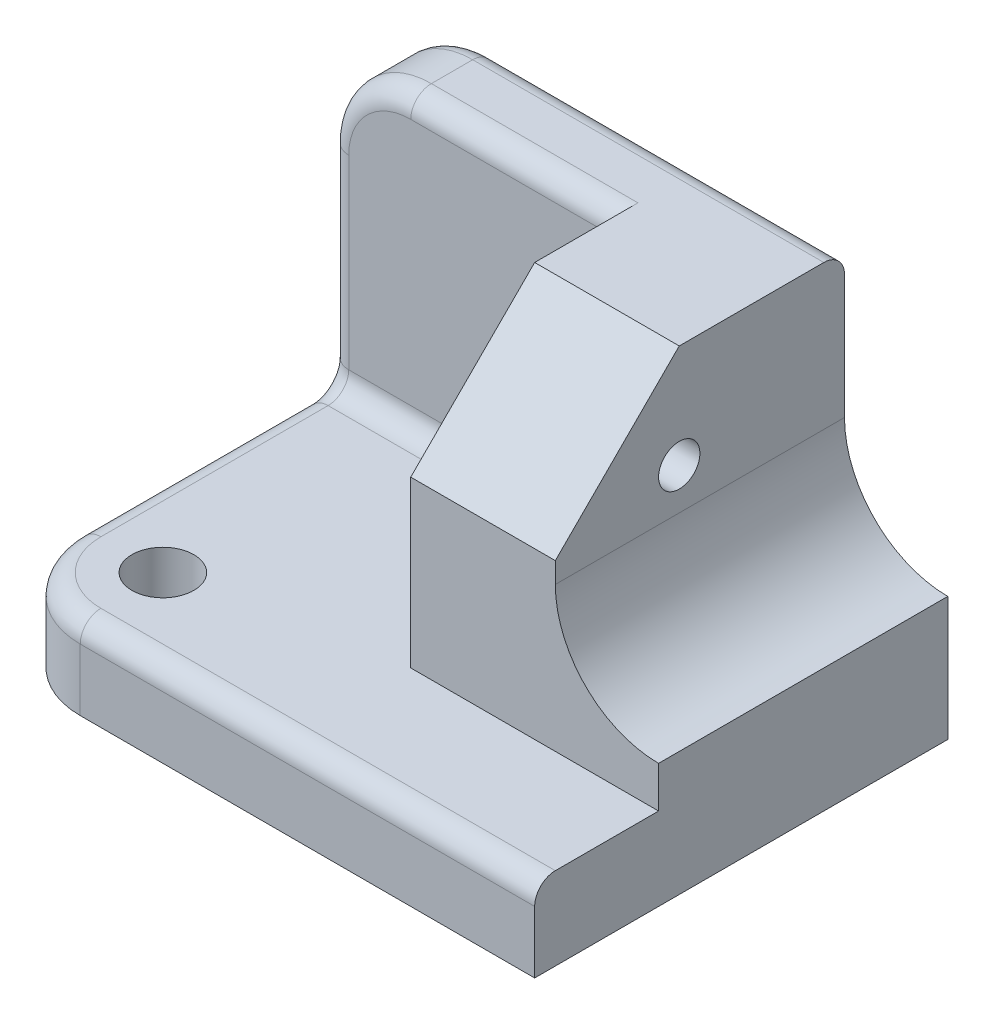
SolidWorks part; units mm, degrees
ref_plane "Front Plane" through (0, 0, 0) normal (0, 0, 1) x (1, 0, 0)
ref_plane "Top Plane" through (0, 0, 0) normal (0, 1, 0) x (1, 0, 0)
ref_plane "Right Plane" through (0, 0, 0) normal (1, 0, 0) x (0, 0, -1)
sketch "Sketch1" plane through (0, 0, 0) normal (0, 1, 0) x (1, 0, 0)
  line L1 (-65, -50) -> (65, -50)
  line L2 (-65, -50) -> (-65, 50)
  line L3 (-65, 50) -> (65, 50)
  line L4 (65, -50) -> (65, 50)
  line L5 (-65, -50) -> (65, 50) construction
  line L6 (-65, 50) -> (65, -50) construction
  point P0 (0, 0)
  dimension "D1" = 100
  dimension "D2" = 130
extrude "Boss-Extrude1" add sketch "Sketch1" along normal blind 20
sketch "Sketch2" plane through (0, 20, 0) normal (0, 1, 0) x (1, 0, 0)
  line L0 (65, -50) -> (65, 50) construction
  line L1 (-65, 50) -> (65, 50)
  line L2 (-65, 50) -> (-65, 30)
  line L3 (-65, 30) -> (65, 30)
  line L4 (65, 50) -> (65, 30)
  dimension "D1" = 20
extrude "Boss-Extrude2" add sketch "Sketch2" along normal blind 70
fillet "Fillet1" radius 20 2 edges at (-65, 10, 50) (-65, 90, -40)
sketch "Sketch3" plane through (0, 0, -30) normal (0, 0, 1) x (1, 0, 0)
  line L0 (-45, 90) -> (65, 90) construction
  line L1 (65, 20) -> (5, 20)
  line L2 (65, 20) -> (65, 90)
  line L3 (65, 90) -> (5, 90)
  line L4 (5, 20) -> (5, 90)
  dimension "D1" = 60
extrude "Boss-Extrude3" add sketch "Sketch3" along normal blind 50
sketch "Sketch4" plane through (0, 0, 20) normal (0, 0, 1) x (1, 0, 0)
  line L0 (40, 90) -> (40, 55)
  line L1 (65, 90) -> (5, 90) construction
  line L2 (65, 20) -> (65, 90) construction
  line L7 (65, 20) -> (65, 90)
  line L8 (65, 90) -> (5, 90)
  line L9 (5, 90) -> (5, 20)
  line L10 (5, 20) -> (65, 20)
  line L11 (65, 30) -> (65, 90)
  line L12 (65, 90) -> (40, 90)
  arc A0 (40, 55) -> (65, 30) centre (65, 55) ccw
  dimension "D2" = 25
  dimension "D1" = 25
  dimension "D3" = 35
  dimension "D4" = 0
extrude "Cut-Extrude1" cut sketch "Sketch4" against normal through all
chamfer "Chamfer1" distance 30 angle 45 1 edges at (22.5, 90, 20)
hole_wizard "Ø10.0 (10) Diameter Hole1" positions "Sketch6" profile "Sketch5" hole size "Ø10.0" standard "ANSI Metric" end condition through all
sketch "Sketch6" plane through (5, 0, 0) normal (-1, 0, 0) x (0, 0, 1)
  line L0 (20, 60) -> (20, 20) construction
  line L1 (20, 20) -> (-30, 20) construction
  point P0 (-10, 65)
  dimension "D1" = 30
  dimension "D2" = 45
sketch "Sketch5" plane through (5, 65, -10) normal (0, 1, 0) x (0, 0, 1)
  line L0 (0, 0) -> (0, 60)
  line L1 (0, 60) -> (5, 60)
  line L2 (5, 60) -> (5, 0)
  line L5 (5, 0) -> (0, 0)
  line L11 (0, -6.35) -> (0, 107.95) construction
  dimension "Thru Hole Dia." = 10
  dimension "Thru Hole Depth" = 60
hole_wizard "Ø15.0 (15) Diameter Hole1" positions "Sketch8" profile "Sketch7" hole size "Ø15.0" standard "ANSI Metric" end condition through all
sketch "Sketch8" plane through (0, 20, 0) normal (0, 1, 0) x (1, 0, 0)
  point P0 (-45, -30)
sketch "Sketch7" plane through (-45, 20, 30) normal (1, 0, 0) x (0, 0, 1)
  line L0 (0, 0) -> (0, 20)
  line L1 (0, 20) -> (7.5, 20)
  line L2 (7.5, 20) -> (7.5, 0)
  line L5 (7.5, 0) -> (0, 0)
  line L11 (0, -6.35) -> (0, 107.95) construction
  dimension "Thru Hole Dia." = 15
  dimension "Thru Hole Depth" = 20
fillet "Fillet2" radius 5 10 edges at (10, 20, 50) (-65, 35, -50) (-2.5, 90, -50) (-20, 90, -30) (-59.1421, 20, 44.1421) (-59.1421, 84.1421, -50) (-59.1421, 84.1421, -30)
